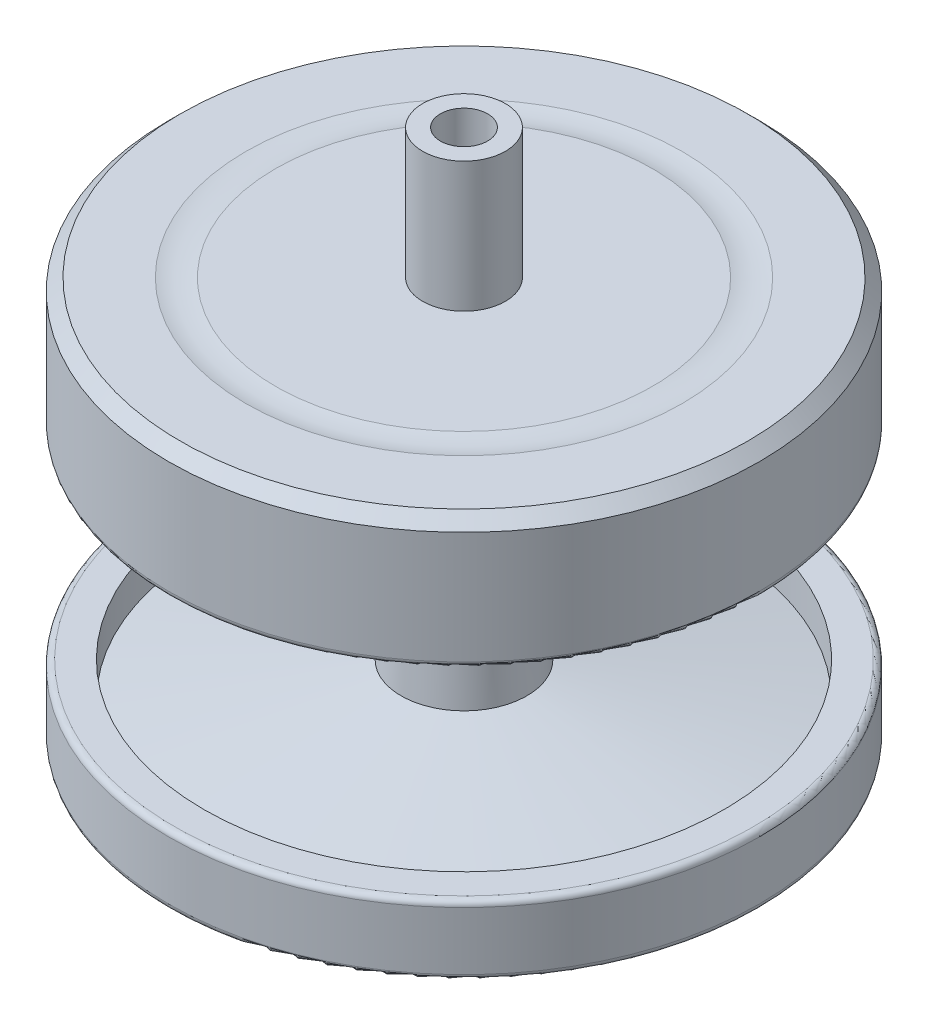
SolidWorks part; units mm, degrees
material "PE(聚乙烯)"
ref_plane "前视" through (0, 0, 0) normal (0, 0, 1) x (1, 0, 0)
ref_plane "上视" through (0, 0, 0) normal (0, 1, 0) x (1, 0, 0)
ref_plane "右视" through (0, 0, 0) normal (1, 0, 0) x (0, 0, -1)
sketch "草图1" plane through (0, 0, 0) normal (0, 0, 1) x (1, 0, 0)
  line L0 (0, 0) -> (0, -44.7555) construction
  line L1 (2, 0) -> (2, -27)
  line L2 (2, 0) -> (3.5, 0)
  line L3 (3.5, 0) -> (3.5, -11)
  line L4 (3.5, -11) -> (25, -11)
  line L5 (25, -11) -> (25, -22)
  line L6 (25, -22) -> (22, -22)
  line L7 (22, -22) -> (22, -14)
  line L8 (22, -14) -> (3.5, -14)
  line L9 (3.5, -14) -> (5.323, -39)
  line L10 (5.323, -39) -> (22, -42)
  line L11 (22, -42) -> (22, -39)
  line L12 (25, -45) -> (6.5, -45)
  line L13 (22, -39) -> (25, -39)
  line L14 (25, -39) -> (25, -45)
  line L15 (2, -27) -> (3.5, -27)
  line L16 (3.5, -27) -> (3.5, -42)
  arc A0 (6.5, -45) -> (3.5, -42) centre (6.5, -42) cw
  dimension "D11" = 3
  dimension "D1" = 4
  dimension "D2" = 7
  dimension "D3" = 11
  dimension "D4" = 50
  dimension "D5" = 11
  dimension "D6" = 44
  dimension "D7" = 3
  dimension "D8" = 6
  dimension "D9" = 34
  dimension "D10" = 3
  dimension "D12" = 7
  dimension "D13" = 18
revolve "旋转1" add sketch "草图1" angle 360 about L0
sketch "草图2" plane through (0, 0, 0) normal (0, 0, 1) x (1, 0, 0)
  line L0 (0, 0) -> (0, -45) construction
  line L1 (3.5, 0) -> (-3.5, 0) construction
  line L2 (-25, -45) -> (25, -45) construction
  line L3 (24, -11) -> (25, -11)
  line L4 (25, -11) -> (-25, -11) construction
  line L5 (25, -22) -> (25, -11) construction
  line L6 (25, -12) -> (25, -11)
  line L7 (24, -11) -> (25, -12)
  line L8 (15.9577, -11) -> (18.4735, -11)
  line L9 (0, -43) -> (-17.4816, -43) construction
  line L10 (0, -43) -> (0, -45)
  line L11 (0, -45) -> (25, -45)
  arc A0 (15.9577, -11) -> (18.4735, -11) centre (17.2156, -5.6442) ccw
  arc A1 (25, -45) -> (0, -43) centre (0, -200.25) ccw
  dimension "D1" = 2
  dimension "D2" = 1
  dimension "D3" = 1
revolve "切除-旋转1" cut sketch "草图2" angle 360 about L0
fillet "圆角1" radius 0.5 3 edges at (-25, -45, 0) (0, -39, 25) (0, -22, 25)
